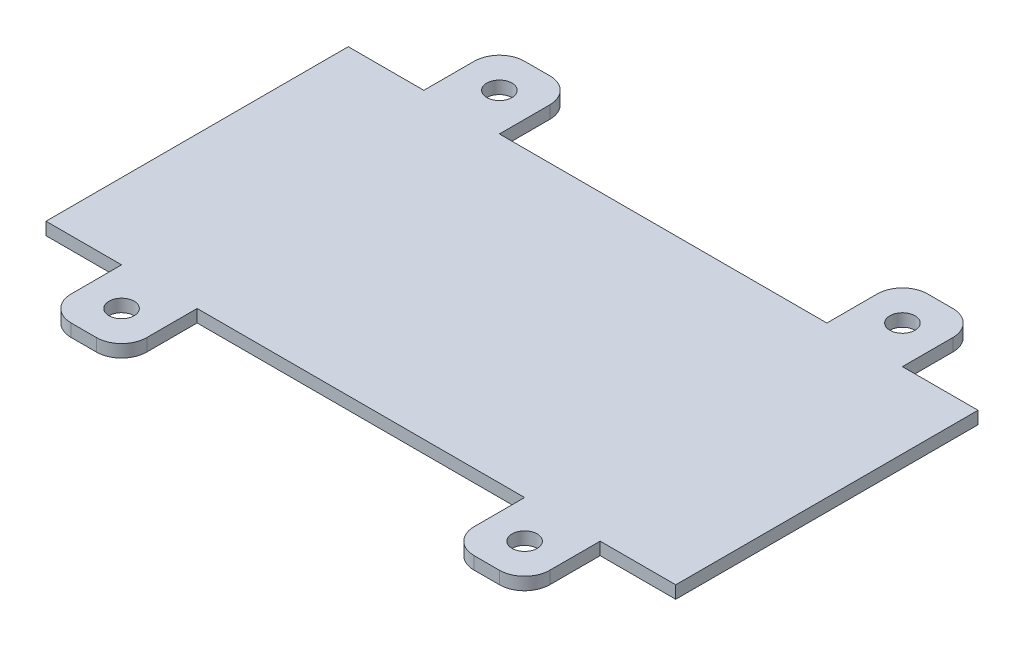
SolidWorks part; units mm, degrees
material "Сталь 3 ГОСТ 535-88"
ref_plane "Спереди" through (0, 0, 0) normal (0, 0, 1) x (1, 0, 0)
ref_plane "Сверху" through (0, 0, 0) normal (0, 1, 0) x (1, 0, 0)
ref_plane "Справа" through (0, 0, 0) normal (1, 0, 0) x (0, 0, -1)
sketch "Эскиз1" plane through (0, 0, 0) normal (0, 1, 0) x (1, 0, 0)
  line L1 (-125, 60) -> (125, 60)
  line L2 (-125, 60) -> (-125, -60)
  line L3 (-125, -60) -> (125, -60)
  line L4 (125, 60) -> (125, -60)
  line L5 (0, -60) -> (0, 60) construction
  line L6 (-125, 0) -> (125, 0) construction
  point P0 (0, 0)
  dimension "D1" = 120
  dimension "D2" = 250
extrude "Бобышка-Вытянуть1" add sketch "Эскиз1" along normal blind 5
sketch "Эскиз2" plane through (0, 0, 0) normal (0, 1, 0) x (1, 0, 0)
  line L0 (125, 60) -> (-125, 60) construction
  line L1 (-95, 60) -> (-65, 60)
  line L2 (-95, 60) -> (-95, 90)
  line L3 (-95, 90) -> (-65, 90)
  line L4 (-65, 60) -> (-65, 90)
  line L5 (-125, 60) -> (-125, -60) construction
  line L6 (-80, 90) -> (-80, 60) construction
  circle A0 centre (-80, 75) radius 5
  dimension "D4" = 10
  dimension "D1" = 30
  dimension "D2" = 30
  dimension "D3" = 30
extrude "Бобышка-Вытянуть2" add sketch "Эскиз2" along normal up to surface (5 mm away) separate body up to face at (0, 5, 0)
fillet "Скругление1" radius 10 2 edges at (-95, 2.5, -90) (-65, 2.5, -90)
mirror "Зеркальное отражение1" about plane through (0, 0, 0) normal (1, 0, 0) of bodies 112
mirror "Зеркальное отражение3" about plane through (0, 0, 0) normal (0, 0, 1) of bodies 112 113
combine bodies "Соединить1" operation type add bodies to combine 107 114 113 112 115
